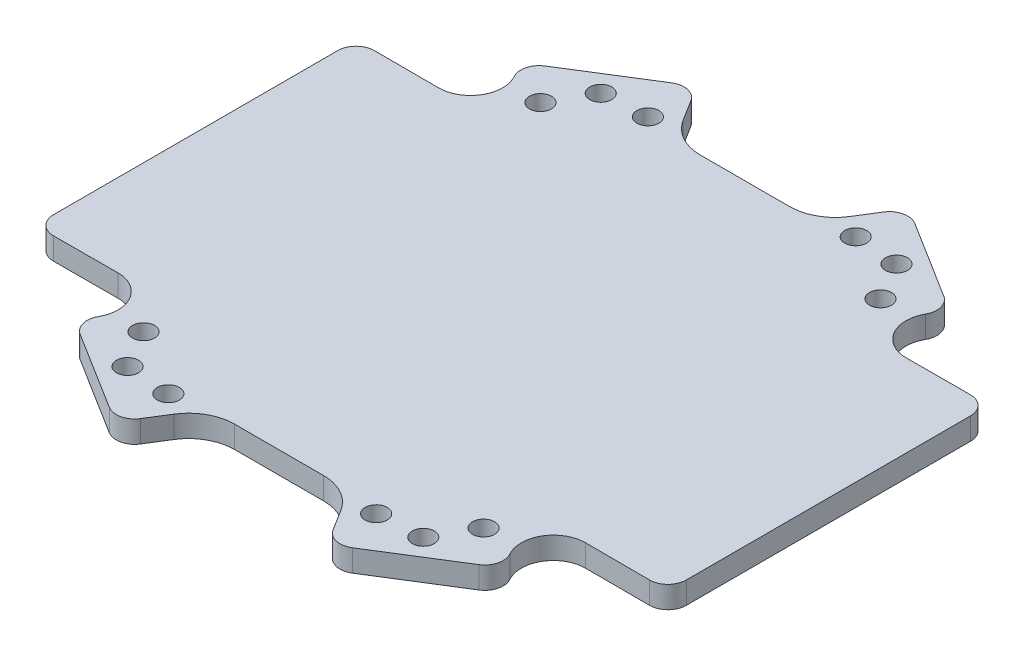
SolidWorks part; units mm, degrees
ref_plane "Front Plane" through (0, 0, 0) normal (0, 0, 1) x (1, 0, 0)
ref_plane "Top Plane" through (0, 0, 0) normal (0, 1, 0) x (1, 0, 0)
ref_plane "Right Plane" through (0, 0, 0) normal (1, 0, 0) x (0, 0, -1)
sketch "Sketch1" plane through (0, 0, 0) normal (0, 1, 0) x (1, 0, 0)
  line L0 (-17.5, 28) -> (-26.4999, 42.3999) construction
  line L1 (-28, 17.5) -> (28, 17.5) construction
  line L2 (-28, 17.5) -> (-28, -17.5) construction
  line L3 (-28, -17.5) -> (28, -17.5) construction
  line L4 (28, 17.5) -> (28, -17.5) construction
  line L5 (-28, 17.5) -> (28, -17.5) construction
  line L6 (-28, -17.5) -> (28, 17.5) construction
  line L7 (-17.5, 28) -> (17.5, 28) construction
  line L8 (-17.5, 28) -> (-17.5, -28) construction
  line L9 (-17.5, -28) -> (17.5, -28) construction
  line L10 (17.5, 28) -> (17.5, -28) construction
  line L11 (-17.5, 28) -> (17.5, -28) construction
  line L12 (-17.5, -28) -> (17.5, 28) construction
  line L13 (17.5, -28) -> (26.4999, -42.3999) construction
  line L14 (-23.436, 24.29) -> (-32.4359, 38.6899) construction
  line L15 (-23.436, 24.29) -> (11.564, -31.71) construction
  line L16 (11.564, -31.71) -> (20.564, -46.1099) construction
  line L17 (-11.564, 31.71) -> (-20.564, 46.1099) construction
  line L18 (-11.564, 31.71) -> (23.436, -24.29) construction
  line L19 (23.436, -24.29) -> (32.4359, -38.6899) construction
  line L20 (0, -28) -> (0, 28) construction
  line L21 (-34.5, 17.5) -> (-34.5, -17.5) construction
  line L22 (-34.5, 0) -> (34.5, 0) construction
  line L24 (34.5, 17.5) -> (34.5, -17.5) construction
  circle A0 centre (-26.4999, 42.3999) radius 25.4 construction
  circle A1 centre (-20, 9.5) radius 8 construction
  circle A2 centre (-26.4999, 42.3999) radius 8 construction
  point P4 (0, 0)
  point P11 (0, 0)
  dimension "D4" = 50.8
  dimension "D7" = 16
  dimension "D10" = 16
  dimension "D1" = 35
  dimension "D2" = 56
  dimension "D3" = 50
  dimension "D8" = 8
  dimension "D9" = 8
  dimension "D11" = 6.5
  dimension "D5" = 7
  dimension "D6" = 7
  dimension "D12" = 6.5
sketch "Sketch2" plane through (0, 0, 0) normal (0, 1, 0) x (1, 0, 0)
  line L0 (-34.5, -17.5) -> (-34.5, 17.5)
  line L1 (-34.5, 17.5) -> (-19.1649, 17.4563)
  line L2 (-23.436, 24.29) -> (11.564, -31.71) construction
  line L3 (-19.1649, 17.4563) -> (-23.436, 24.29)
  line L4 (-23.436, 24.29) -> (-11.564, 31.71)
  line L5 (-11.564, 31.71) -> (-7.6233, 25.4049)
  line L6 (-11.564, 31.71) -> (23.436, -24.29) construction
  line L7 (-7.6233, 25.4049) -> (7.6233, 25.4049)
  line L8 (0, -28) -> (0, 28) construction
  line L9 (0, -28) -> (0, 28) construction
  line L10 (-34.5, 0) -> (34.5, 0) construction
  line L11 (34.5, 17.5) -> (34.5, -17.5) construction
  line L12 (34.5, -17.5) -> (34.5, 17.5)
  line L13 (11.564, 31.71) -> (7.6233, 25.4049)
  line L14 (23.436, 24.29) -> (11.564, 31.71)
  line L15 (19.1649, 17.4563) -> (23.436, 24.29)
  line L16 (34.5, 17.5) -> (19.1649, 17.4563)
  line L17 (34.5, -17.5) -> (19.1649, -17.4563)
  line L18 (19.1649, -17.4563) -> (23.436, -24.29)
  line L19 (23.436, -24.29) -> (11.564, -31.71)
  line L20 (11.564, -31.71) -> (7.6233, -25.4049)
  line L21 (-7.6233, -25.4049) -> (7.6233, -25.4049)
  line L22 (-11.564, -31.71) -> (-7.6233, -25.4049)
  line L23 (-23.436, -24.29) -> (-11.564, -31.71)
  line L24 (-19.1649, -17.4563) -> (-23.436, -24.29)
  line L25 (-34.5, -17.5) -> (-19.1649, -17.4563)
  circle A0 centre (-20, 9.5) radius 8 construction
  circle A1 centre (-26.4999, 42.3999) radius 25.4 construction
  point P29 (0, 25.4049)
  point P43 (0, -25.4049)
extrude "Boss-Extrude1" add sketch "Sketch2" along normal mid plane 2.4
fillet "Fillet1" radius 3.5 4 edges at (19.1649, 0, 17.4563) (-19.1649, 0, 17.4563) (19.1649, 0, -17.4563) (-19.1649, 0, -17.4563)
fillet "Fillet2" radius 5 4 edges at (7.6233, 0, 25.4049) (-7.6233, 0, 25.4049) (7.6233, 0, -25.4049) (-7.6233, 0, -25.4049)
fillet "Fillet3" radius 2 12 edges at (34.5, 0, -17.5) (23.436, 0, -24.29) (34.5, 0, 17.5) (23.436, 0, 24.29) (11.564, 0, 31.71) (11.564, 0, -31.71) (-11.564, 0, -31.71) (-23.436, 0, -24.29) (-34.5, 0, -17.5) (-34.5, 0, 17.5) (-11.564, 0, 31.71) (-23.436, 0, 24.29)
sketch "Sketch3" plane through (0, 1.2, 0) normal (0, 1, 0) x (1, 0, 0)
  line L0 (-19.4953, 17.9849) -> (-7.6233, 25.4049) construction
  line L1 (-23.436, 24.29) -> (11.564, -31.71) construction
  line L2 (-11.564, 31.71) -> (23.436, -24.29) construction
  line L3 (-18.5386, 21.6429) -> (-16.1271, 25.8034) construction
  line L4 (-17.5, 28) -> (17.5, -28) construction
  line L5 (-18.5386, 21.6429) -> (-11.3306, 26.1479) construction
  line L6 (-11.3306, 26.1479) -> (-16.1271, 25.8034) construction
  circle A0 centre (-26.4999, 42.3999) radius 25.4 construction
  circle A1 centre (-16.1271, 25.8034) radius 1.2
  circle A2 centre (-11.3306, 26.1479) radius 1.2
  circle A3 centre (-18.5386, 21.6429) radius 1.2
  circle A4 centre (-18.5386, 21.6429) radius 1.9 construction
  circle A5 centre (-16.1271, 25.8034) radius 1.9 construction
  circle A6 centre (-11.3306, 26.1479) radius 1.9 construction
  point P12 (-14.9346, 23.8954)
  dimension "D2" = 2.4
  dimension "D5" = 3.8
  dimension "D1" = 4.25
  dimension "D3" = 2.25
  dimension "D4" = 2.595
extrude "Cut-Extrude1" cut sketch "Sketch3" against normal through all
mirror "Mirror1" about plane through (0, 0, 0) normal (1, 0, 0) of "Cut-Extrude1"
mirror "Mirror2" about plane through (0, 0, 0) normal (0, 0, 1) of "Cut-Extrude1", "Mirror1"
equation "\"D4@Sketch3\"=(7.44-\"D3@Sketch3\")/2"
